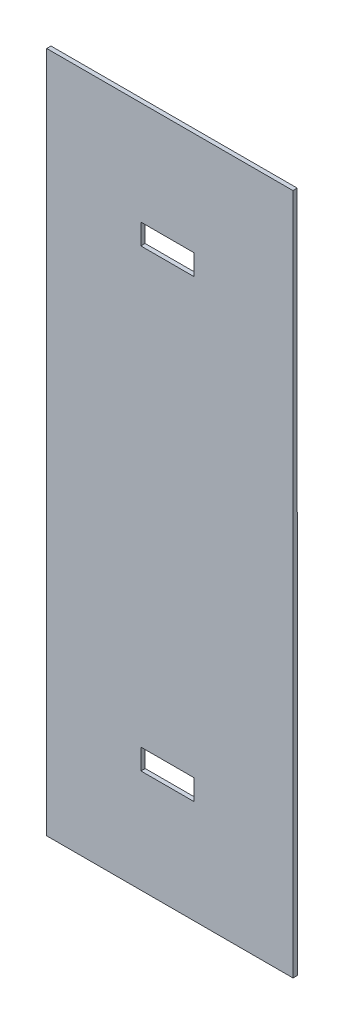
SolidWorks part; units mm, degrees
ref_plane "Front Plane" through (0, 0, 0) normal (0, 0, 1) x (1, 0, 0)
ref_plane "Top Plane" through (0, 0, 0) normal (0, 1, 0) x (1, 0, 0)
ref_plane "Right Plane" through (0, 0, 0) normal (1, 0, 0) x (0, 0, -1)
sketch "Sketch1" plane through (0, 0, 0) normal (0, 0, 1) x (1, 0, 0)
  line L0 (989.7538, 1584.4023) -> (816.7133, 1584.3406) construction
  line L1 (920.2767, 1431.9433) -> (882.9332, 1431.9129)
  line L2 (920.2885, 1417.4201) -> (920.2767, 1431.9433)
  line L3 (882.9451, 1417.3897) -> (920.2885, 1417.4201)
  line L4 (882.9332, 1431.9129) -> (882.9451, 1417.3897)
  line L5 (882.9332, 1431.9129) -> (882.9451, 1417.3897)
  line L6 (882.9451, 1417.3897) -> (920.2885, 1417.4201)
  line L7 (920.2885, 1417.4201) -> (920.2767, 1431.9433)
  line L8 (920.2767, 1431.9433) -> (882.9332, 1431.9129)
  line L1932 (989.7944, 1344.8701) -> (989.7133, 1823.9344)
  line L1933 (989.7133, 1823.9344) -> (816.7133, 1823.8727)
  line L1934 (816.7133, 1823.8727) -> (816.7133, 1344.8084)
  line L1935 (816.7133, 1344.8084) -> (989.7944, 1344.8701)
  line L1940 (882.8245, 1736.8153) -> (882.826, 1751.3386)
  line L1941 (882.826, 1751.3386) -> (920.1695, 1751.3348)
  line L1942 (920.1695, 1751.3348) -> (920.168, 1736.8116)
  line L1943 (920.168, 1736.8116) -> (882.8245, 1736.8153)
  line L1944 (870.5555, 1765.2192) -> (827.0776, 1765.2192)
  line L1945 (827.0776, 1722.8968) -> (870.5572, 1722.8968)
  spline S1652 degree 3 poles (891.7167, 1744.0563) (891.7167, 1755.7433) (882.2441, 1765.2192) (870.5555, 1765.2192) knots 0 0 0 0 1 1 1 1
  spline S1653 degree 3 poles (827.0776, 1765.2192) (815.389, 1765.2192) (805.913, 1755.7449) (805.913, 1744.0563) knots 2 2 2 2 3 3 3 3
  spline S1654 degree 3 poles (805.913, 1744.0563) (805.913, 1732.3711) (815.3856, 1722.8968) (827.0776, 1722.8968) knots 4 4 4 4 5 5 5 5
  spline S1655 degree 3 poles (870.5572, 1722.8968) (882.2441, 1722.9051) (891.7167, 1732.3794) (891.7167, 1744.0563) knots 6 6 6 6 7 7 7 7
  point P7 (0, 0)
  dimension "D1" = 479.0643
  dimension "D3" = 37.3435
  dimension "D4" = 72.5577
  dimension "D5" = 69.56
  dimension "D6" = 173
extrude "Boss-Extrude1" add sketch "Sketch1" along normal blind 3
